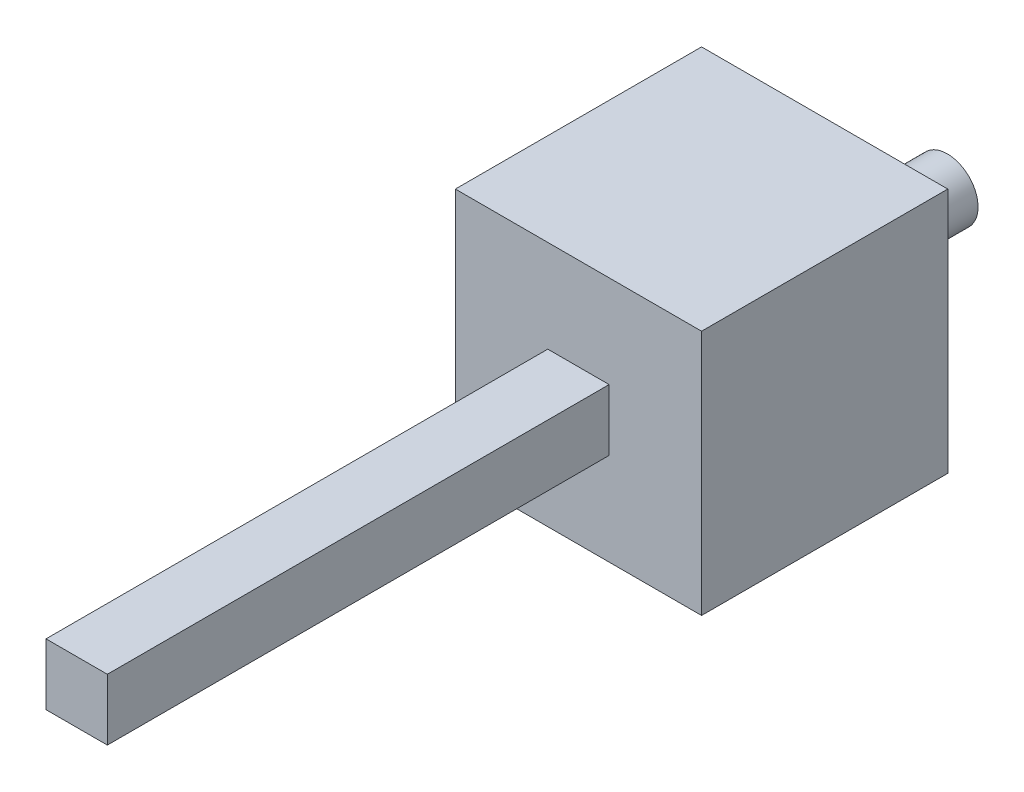
SolidWorks part; units mm, degrees
ref_plane "Alzado" through (0, 0, 0) normal (0, 0, 1) x (1, 0, 0)
ref_plane "Planta" through (0, 0, 0) normal (0, 1, 0) x (1, 0, 0)
ref_plane "Vista lateral" through (0, 0, 0) normal (1, 0, 0) x (0, 0, -1)
sketch "Croquis1" plane through (0, 0, 0) normal (0, 0, 1) x (1, 0, 0)
  line L1 (1.0033, -1.0033) -> (-1.0033, -1.0033)
  line L2 (1.0033, -1.0033) -> (1.0033, 1.0033)
  line L3 (1.0033, 1.0033) -> (-1.0033, 1.0033)
  line L4 (-1.0033, -1.0033) -> (-1.0033, 1.0033)
  line L5 (1.0033, -1.0033) -> (-1.0033, 1.0033) construction
  line L6 (1.0033, 1.0033) -> (-1.0033, -1.0033) construction
  point P0 (0, 0)
  dimension "D1" = 2.0066
extrude "Saliente-Extruir1" add sketch "Croquis1" along normal blind 2.0066
sketch "Croquis3" plane through (0, 0, 0) normal (0, 0, -1) x (-1, 0, 0)
  line L1 (-0.25, 0.25) -> (-0.25, -0.25)
  line L2 (-0.25, -0.25) -> (0.25, -0.25)
  line L3 (0.25, -0.25) -> (0.25, 0.25)
  line L4 (0.25, 0.25) -> (-0.25, 0.25)
  circle A1 centre (0, 0) radius 0.25 construction
  point P1 (-0.5, -0.5)
  dimension "D1" = 0.5
extrude "Saliente-Extruir3" add sketch "Croquis3" against normal blind 6.096
sketch "Croquis4" plane through (0, 0, 0) normal (0, 0, -1) x (-1, 0, 0)
  circle A0 centre (0, 0) radius 0.25
  dimension "D1" = 0.5
extrude "Saliente-Extruir4" add sketch "Croquis4" along normal blind 1
